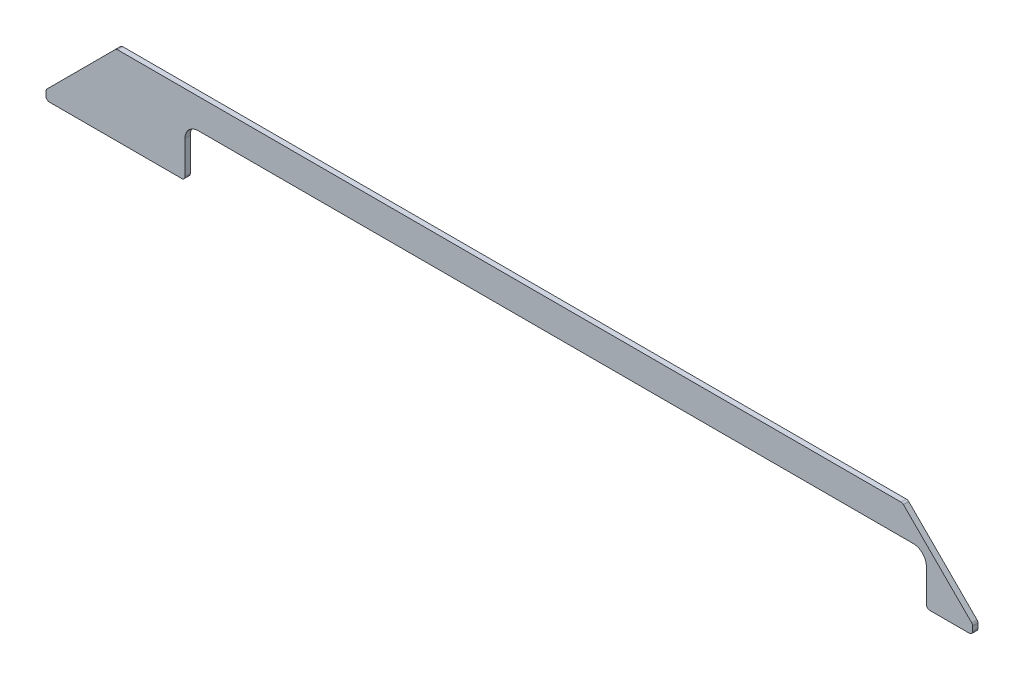
SolidWorks part; units mm, degrees
ref_plane "Front Plane" through (0, 0, 0) normal (0, 0, 1) x (1, 0, 0)
ref_plane "Top Plane" through (0, 0, 0) normal (0, 1, 0) x (1, 0, 0)
ref_plane "Right Plane" through (0, 0, 0) normal (1, 0, 0) x (0, 0, -1)
sketch "Sketch1" plane through (0, 0, 0) normal (0, 0, 1) x (1, 0, 0)
  line L0 (0, 2.7868) -> (21.2132, 24)
  line L1 (0, 0) -> (280, 0)
  line L2 (0, 0) -> (0, 24)
  line L3 (0, 24) -> (280, 24)
  line L4 (280, 0) -> (280, 24)
  line L5 (42, 0) -> (266, 0)
  line L6 (42, 0) -> (42, 11)
  line L7 (46, 15) -> (262, 15)
  line L8 (266, 0) -> (266, 11)
  line L9 (280, 2.7868) -> (258.7868, 24)
  arc A0 (262, 15) -> (266, 11) centre (262, 11) cw
  arc A1 (42, 11) -> (46, 15) centre (46, 11) cw
  dimension "D3" = 4
  dimension "D1" = 45
  dimension "D2" = 45
  dimension "D4" = 224
  dimension "D5" = 15
  dimension "D6" = 280
  dimension "D7" = 30
  dimension "D8" = 30
  dimension "D9" = 24
  dimension "D10" = 42
extrude "Boss-Extrude1" add sketch "Sketch1" along normal blind 1.6 contours L6 A1 L7 A0 L8 L1 L4 L9 L3 L0 L2
fillet "Fillet1" radius 1 8 edges at (258.7868, 24, 0.8) (280, 0, 0.8) (280, 2.7868, 0.8) (266, 0, 0.8) (42, 0, 0.8) (0, 2.7868, 0.8) (0, 0, 0.8) (21.2132, 24, 0.8)
sketch "Sketch2" plane through (0, 0, 0) normal (0, 0, 1) x (1, 0, 0)
  line L0 (46, 15) -> (262, 15) construction
  line L1 (62.01, 3.3) -> (65.99, 3.3)
  line L2 (62.01, 3.3) -> (62.01, 5)
  line L3 (62.01, 5) -> (65.99, 5)
  line L4 (65.99, 3.3) -> (65.99, 5)
  line L5 (46, 3.3) -> (58.4, 3.3)
  line L6 (46, 3.3) -> (46, 9.05)
  line L7 (46, 9.05) -> (58.4, 9.05)
  line L8 (58.4, 3.3) -> (58.4, 9.05)
  line L9 (82.01, 3.3) -> (85.99, 3.3)
  line L10 (82.01, 3.3) -> (82.01, 5)
  line L11 (82.01, 5) -> (85.99, 5)
  line L12 (85.99, 3.3) -> (85.99, 5)
  line L13 (102.01, 3.3) -> (105.99, 3.3)
  line L14 (102.01, 3.3) -> (102.01, 5)
  line L15 (102.01, 5) -> (105.99, 5)
  line L16 (105.99, 3.3) -> (105.99, 5)
  line L17 (122.01, 3.3) -> (125.99, 3.3)
  line L18 (122.01, 3.3) -> (122.01, 5)
  line L19 (122.01, 5) -> (125.99, 5)
  line L20 (125.99, 3.3) -> (125.99, 5)
  line L21 (142.01, 3.3) -> (145.99, 3.3)
  line L22 (142.01, 3.3) -> (142.01, 5)
  line L23 (142.01, 5) -> (145.99, 5)
  line L24 (145.99, 3.3) -> (145.99, 5)
  line L25 (162.01, 3.3) -> (165.99, 3.3)
  line L26 (162.01, 3.3) -> (162.01, 5)
  line L27 (162.01, 5) -> (165.99, 5)
  line L28 (165.99, 3.3) -> (165.99, 5)
  line L29 (182.01, 3.3) -> (185.99, 3.3)
  line L30 (182.01, 3.3) -> (182.01, 5)
  line L31 (182.01, 5) -> (185.99, 5)
  line L32 (185.99, 3.3) -> (185.99, 5)
  line L33 (202.01, 3.3) -> (205.99, 3.3)
  line L34 (202.01, 3.3) -> (202.01, 5)
  line L35 (202.01, 5) -> (205.99, 5)
  line L36 (205.99, 3.3) -> (205.99, 5)
  line L37 (222.01, 3.3) -> (225.99, 3.3)
  line L38 (222.01, 3.3) -> (222.01, 5)
  line L39 (222.01, 5) -> (225.99, 5)
  line L40 (225.99, 3.3) -> (225.99, 5)
  line L41 (242.01, 3.3) -> (245.99, 3.3)
  line L42 (242.01, 3.3) -> (242.01, 5)
  line L43 (242.01, 5) -> (245.99, 5)
  line L44 (245.99, 3.3) -> (245.99, 5)
  line L45 (62.01, 3.3) -> (82.01, 3.3) construction
  line L46 (145.99, 3.3) -> (162.01, 3.3)
  line L47 (249.6, 3.3) -> (262, 3.3)
  line L48 (249.6, 3.3) -> (249.6, 9.05)
  line L49 (249.6, 9.05) -> (262, 9.05)
  line L50 (262, 3.3) -> (262, 9.05)
  line L51 (42, 0) -> (42, 11) construction
  line L52 (266, 0) -> (266, 11) construction
  point P10 (154, 3.3)
  point P49 (154, 15)
  dimension "D1" = 3.98
  dimension "D2" = 1.7
  dimension "D3" = 12.4
  dimension "D4" = 5.75
  dimension "D5" = 10
  dimension "D7" = 20
  dimension "D8" = 12.4
  dimension "D9" = 5.75
  dimension "D10" = 4
  dimension "D11" = 4
  dimension "D6" = 10
